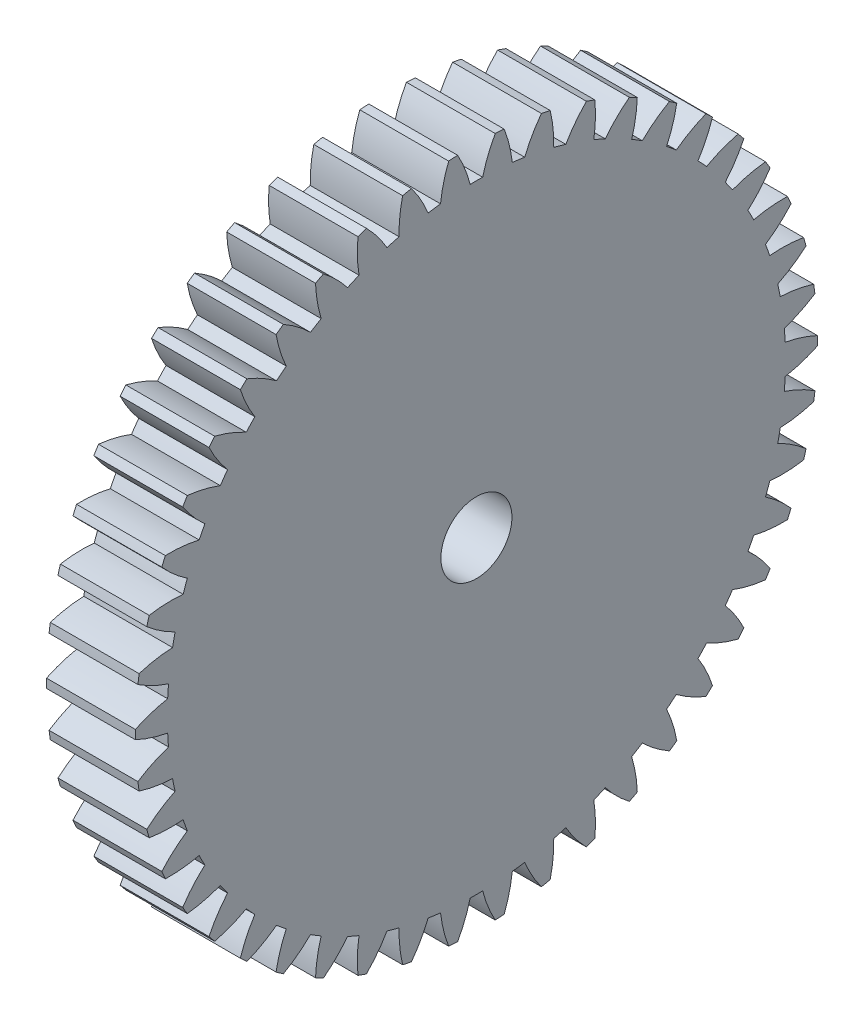
SolidWorks part; units mm, degrees
ref_plane "Plane1" through (0, 0, 0) normal (0, 0, 1) x (1, 0, 0)
ref_plane "Plane2" through (0, 0, 0) normal (0, 1, 0) x (1, 0, 0)
ref_plane "Plane3" through (0, 0, 0) normal (1, 0, 0) x (0, 0, -1)
sketch "HoldingSke" plane through (0, 0, 0) normal (0, 1, 0) x (1, 0, 0)
  line L0 (0, 0) -> (0.8683, -0.8992)
  line L1 (-15, 0) -> (100, 0) construction
  line L2 (0, 0) -> (-2.1039, 2.3779)
  line L3 (0, 0) -> (-11.863, 4.5341)
  line L4 (0, 0) -> (5.9991, 6.2122)
  line L5 (0, 0) -> (-46.8476, -17.4728)
  line L6 (0, 0) -> (-4.1448, -2.7965)
  line L7 (-2.1039, 2.3779) -> (8.6586, 51.2059)
  line L8 (-76.2, 54.61) -> (-75.5, 54.61)
  line L9 (-71.009, 38.7566) -> (-53.1078, 45.2721)
  line L10 (-76.2, 71.12) -> (104.1128, 71.12)
  line L11 (0, 0) -> (-5, 0)
  line L12 (-76.2, 101.6) -> (-76.17, 101.6)
  line L13 (24.9733, 27.94) -> (52.9518, 28.4284)
  line L14 (24.9733, 27.94) -> (24.9743, 27.94)
  line L15 (24.9733, 27.94) -> (100.4006, 29.5858)
  line L16 (-63.627, -0.8) -> (-12.827, -0.8)
  circle A0 centre (0, 0) radius 2
  circle A1 centre (0, 0) radius 17.399
  circle A2 centre (0, 0) radius 37.5
  circle A3 centre (0, 0) radius 2
  dimension "MHD" = 34.798
  dimension "Hub_dia" = 75
  dimension "Bore" = 4
  dimension "MBD" = 4
  dimension "Num_teeth" = 46
  dimension "Pitch" = 1.25
  dimension "Overall_len" = 50
  dimension "Show_teeth" = 46
  dimension "Thickness" = 5
  dimension "OAL" = 50.0001
  dimension "T_dim" = 0.7
  dimension "Ap" = 20
  dimension "H" = 19.05
  dimension "Pitch_radius" = 180.3128
  dimension "Width" = 5
  dimension "Backlash" = 0.03
  dimension "Addendum_fac" = 1
  dimension "Dedendum_fac" = 1.25
  dimension "Clearance_fac" = 0.25
  dimension "Dedendum_add" = 0.001
  dimension "Module" = 0.8
sketch "BasProSke" plane through (0, 0, 0) normal (0, 1, 0) x (1, 0, 0)
  line L0 (-10, 0) -> (60, 0) construction
  line L1 (0, 0) -> (0, 19.2)
  line L2 (0, 0) -> (5, 0)
  line L3 (5, 0) -> (5, 19.2)
  line L4 (5, 19.2) -> (0, 19.2)
  dimension "Thickness" = 5
  dimension "Diameter" = 38.4
revolve "Base-Revolve" add sketch "BasProSke" angle 360 about L0
sketch "TooCutSke" plane through (0, 0, 0) normal (1, 0, 0) x (0, 0, -1)
  line L1 (0, 0) -> (0, 107) construction
  line L2 (0, 0) -> (-0.6807, 18.3874) construction
  line L3 (0, 0) -> (-2.5101, 36.6962) construction
  line L4 (-0.6807, 18.3874) -> (-1.255, 18.3481) construction
  arc A0 (0.3525, 17.3954) -> (-0.3525, 17.3954) centre (0, 0) ccw
  arc A1 (1.0726, 19.1955) -> (-1.0726, 19.1955) centre (0, 0) ccw
  circle A2 centre (0, 0) radius 18.4 construction
  circle A3 centre (0, 0) radius 17.2903 construction
  arc A4 (-0.3525, 17.3954) -> (-1.0726, 19.1955) centre (-7.4865, 15.5855) ccw
  arc A5 (1.0726, 19.1955) -> (0.3525, 17.3954) centre (7.4865, 15.5855) ccw
  dimension "Root_dia" = 34.798
  dimension "Overcut_dia" = 38.4508
  dimension "Pitch_dia" = 36.8
  dimension "Base_dia" = 34.5807
  dimension "Flank_rad" = 7.36
  dimension "Half_ang" = 3.913
  dimension "Half_CT" = 0.5757
extrude "ToothCut" cut sketch "TooCutSke" along normal through all
fillet "Breaks" [suppressed] radius 0.016
fillet "RootFillets" [suppressed] radius 0.201
pattern_circular "TeethCuts" count 46 every 7.826 about axis through (-10, 0, 0) along (1, 0, 0) of "ToothCut", "RootFillets", "Breaks"
sketch "HubNeaOneSke" plane through (0, 0, 0) normal (-1, 0, 0) x (0, 0, 1)
  circle A0 centre (0, 0) radius 17.399
  dimension "Diameter" = 34.798
extrude "HubNearOne" [suppressed] add sketch "HubNeaOneSke" along normal blind 45.0001
sketch "HubNeaBotSke" plane through (0, 0, 0) normal (-1, 0, 0) x (0, 0, 1)
  circle A0 centre (0, 0) radius 17.399
  dimension "Diameter" = 34.798
extrude "HubNearBoth" [suppressed] add sketch "HubNeaBotSke" along normal blind 22.5
ref_plane "FarPln" through (5, 0, 0) normal (1, 0, 0) x (0, 0, -1)
sketch "HubFarSke" plane through (5, 0, 0) normal (1, 0, 0) x (0, 0, -1)
  circle A0 centre (0, 0) radius 17.399
  dimension "Diameter" = 34.798
extrude "HubFar" [suppressed] add sketch "HubFarSke" along normal blind 22.5
sketch "BorSke" plane through (0, 0, 0) normal (1, 0, 0) x (0, 0, -1)
  circle A0 centre (0, 0) radius 2
  dimension "Diameter" = 4
extrude "Bore" cut sketch "BorSke" along normal mid plane 100.0001
sketch "KeySke" plane through (0, 0, 0) normal (1, 0, 0) x (0, 0, -1)
  line L0 (-0.8, 0) -> (-0.8, 2.7)
  line L1 (-0.8, 2.7) -> (0.8, 2.7)
  line L2 (0.8, 2.7) -> (0.8, 0)
  line L3 (0, 0) -> (0, 34) construction
  line L4 (-0.8, 0) -> (0.8, 0)
  dimension "Offset" = 2.7
  dimension "Width" = 1.6
extrude "Keyway" [suppressed] cut sketch "KeySke" along normal mid plane 100.0001
pattern_circular "Keyway2" [suppressed] count 2 every 90 about axis through (-10, 0, 0) along (1, 0, 0)
equation "' \"Module@HoldingSke\" = 6.35"
equation "' \"Num_teeth@HoldingSke\" = 12"
equation "' \"Ap@HoldingSke\" =  20"
equation "' \"Ap@HoldingSke\" = 20"
equation "' \"Width@HoldingSke\" = 0.5 * 25.4"
equation "' \"Hub_dia@HoldingSke\"= 1 * 25.4"
equation "' \"Hub_dia@HoldingSke\" = 1 * 25.4"
equation "' \"Overall_len@HoldingSke\" = 1.0 * 25.4"
equation "' \"Bore@HoldingSke\" = 0.75 * 25.4"
equation "' \"T_dim@HoldingSke\" = 0.1 * 25.4"
equation "' \"Width@KeySke\" = 0.25 * 25.4"
equation "' \"Show_teeth@HoldingSke\" = 13"
equation "' \"Backlash@HoldingSke\" = 0.009 * 25.4"
equation "' \"Addendum_fac@HoldingSke\" = 1.0"
equation "' \"Dedendum_fac@HoldingSke\" = 1.25"
equation "' \"Dedendum_add@HoldingSke\" = 0.00005 * 25.4"
equation "' \"Clearance_fac@HoldingSke\" = 0.25"
equation "\"Pitch@HoldingSke\" = 1 / \"Module@HoldingSke\""
equation "\"Overcut_dia@TooCutSke\" = (\"Num_teeth@HoldingSke\" + 2 * \"Addendum_fac@HoldingSke\") / \"Pitch@HoldingSke\" + 0.002 * 25.4"
equation "\"Pitch_dia@TooCutSke\" = \"Num_teeth@HoldingSke\" / \"Pitch@HoldingSke\""
equation "\"Base_dia@TooCutSke\" = \"Num_teeth@HoldingSke\" / \"Pitch@HoldingSke\" * cos((\"Ap@HoldingSke\"  * 3.14159265 / 180))"
equation "\"Root_dia@TooCutSke\" = (\"Num_teeth@HoldingSke\" + 2) / \"Pitch@HoldingSke\" - 2 * (\"Addendum_fac@HoldingSke\" + \"Dedendum_fac@HoldingSke\") / \"Pitch@HoldingSke\" - \"Dedendum_add@HoldingSke\" * 2"
equation "\"Half_ang@TooCutSke\" = 180 / \"Num_teeth@HoldingSke\""
equation "\"Half_CT@TooCutSke\" = \"Num_teeth@HoldingSke\" / \"Pitch@HoldingSke\" * sin((3.14159265 / 2 / \"Num_teeth@HoldingSke\")) / 2 - 7 * \"Backlash@HoldingSke\" / 4"
equation "\"Flank_rad@TooCutSke\" = \"Num_teeth@HoldingSke\" / \"Pitch@HoldingSke\" / 5"
equation "\"Radius@RootFillets\" = \"Clearance_fac@HoldingSke\" / \"Pitch@HoldingSke\" + \"Dedendum_add@HoldingSke\""
equation "\"Break_rad@Breaks\" = 0.02 / \"Pitch@HoldingSke\""
equation "\"Thickness@HoldingSke\" = \"Width@HoldingSke\""
equation "\"OAL@HoldingSke\" = \"Thickness@HoldingSke\""
equation "\"MHD@HoldingSke\" = (\"Num_teeth@HoldingSke\" + 2) / \"Pitch@HoldingSke\" - 2 * (\"Addendum_fac@HoldingSke\" + \"Dedendum_fac@HoldingSke\")  / \"Pitch@HoldingSke\" - \"Dedendum_add@HoldingSke\" * 2"
equation "\"MBD@HoldingSke\" = (\"Num_teeth@HoldingSke\" + 2) / \"Pitch@HoldingSke\" - 2 * (\"Addendum_fac@HoldingSke\" + \"Dedendum_fac@HoldingSke\")  / \"Pitch@HoldingSke\" - \"Dedendum_add@HoldingSke\" * 2 - 0.002 * 25.4"
equation "\"MHD@HoldingSke\" = ((sgn( \"MHD@HoldingSke\" - \"Hub_dia@HoldingSke\" )-1)*( \"MHD@HoldingSke\" - \"Hub_dia@HoldingSke\" ))/-2+ \"Hub_dia@HoldingSke\""
equation "\"MBD@HoldingSke\" = ((sgn( \"MBD@HoldingSke\" - \"Bore@HoldingSke\" )-1)*( \"MBD@HoldingSke\" - \"Bore@HoldingSke\" ))/-2+ \"Bore@HoldingSke\""
equation "\"OAL@HoldingSke\" = ((sgn( \"OAL@HoldingSke\" - \"Overall_len@HoldingSke\" )+1)*( \"OAL@HoldingSke\" - \"Overall_len@HoldingSke\" ))/2 + \"Overall_len@HoldingSke\" + 0.000002 * 25.4"
equation "\"Num_teeth@TeethCuts\" = int( \"Show_teeth@HoldingSke\" ) + 1"
equation "\"Num_teeth@TeethCuts\" = ((sgn( \"Num_teeth@TeethCuts\" - \"Num_teeth@HoldingSke\" )-1)*( \"Num_teeth@TeethCuts\" - \"Num_teeth@HoldingSke\" ))/-2+ \"Num_teeth@HoldingSke\""
equation "\"Num_teeth@TeethCuts\" = ((sgn( \"Num_teeth@TeethCuts\" - 2.0)+1)*( \"Num_teeth@TeethCuts\" - 2.0))/2 +2.0"
equation "\"Angle@TeethCuts\" = 360.0 / \"Num_teeth@HoldingSke\""
equation "\"Diameter@BasProSke\" = (\"Num_teeth@HoldingSke\" + 2 * \"Addendum_fac@HoldingSke\") / \"Pitch@HoldingSke\""
equation "\"Thickness@BasProSke\"  = \"Thickness@HoldingSke\""
equation "' \"Fillet_rad@BasProSke\" =  \"Thickness@HoldingSke\" * 0.05"
equation "' \"Fillet_rad@BasProSke\" = \"Thickness@HoldingSke\" * 0.05"
equation "\"MHD@HoldingSke\" = ((sgn( \"MHD@HoldingSke\" - \"Root_dia@TooCutSke\" )-1)*( \"MHD@HoldingSke\" - \"Root_dia@TooCutSke\" ))/-2+ \"Root_dia@TooCutSke\""
equation "\"Diameter@HubNeaOneSke\" = \"MHD@HoldingSke\""
equation "\"Length@HubNearOne\" = \"OAL@HoldingSke\" - \"Thickness@BasProSke\""
equation "\"Diameter@HubNeaBotSke\" = \"MHD@HoldingSke\""
equation "\"Length@HubNearBoth\" = ( \"OAL@HoldingSke\" - \"Thickness@BasProSke\" ) / 2.0"
equation "\"Thickness@FarPln\" = \"Thickness@BasProSke\""
equation "\"Diameter@HubFarSke\" = \"MHD@HoldingSke\""
equation "\"Length@HubFar\" = ( \"OAL@HoldingSke\" - \"Thickness@BasProSke\" ) / 2.0"
equation "\"Diameter@BorSke\" = \"MBD@HoldingSke\""
equation "\"D1@Bore\" = \"OAL@HoldingSke\" * 2.0"
equation "\"D1@Keyway\" = \"OAL@HoldingSke\" * 2.0"
equation "\"Offset@KeySke\" = \"T_dim@HoldingSke\" + \"MBD@HoldingSke\" / 2.0"
